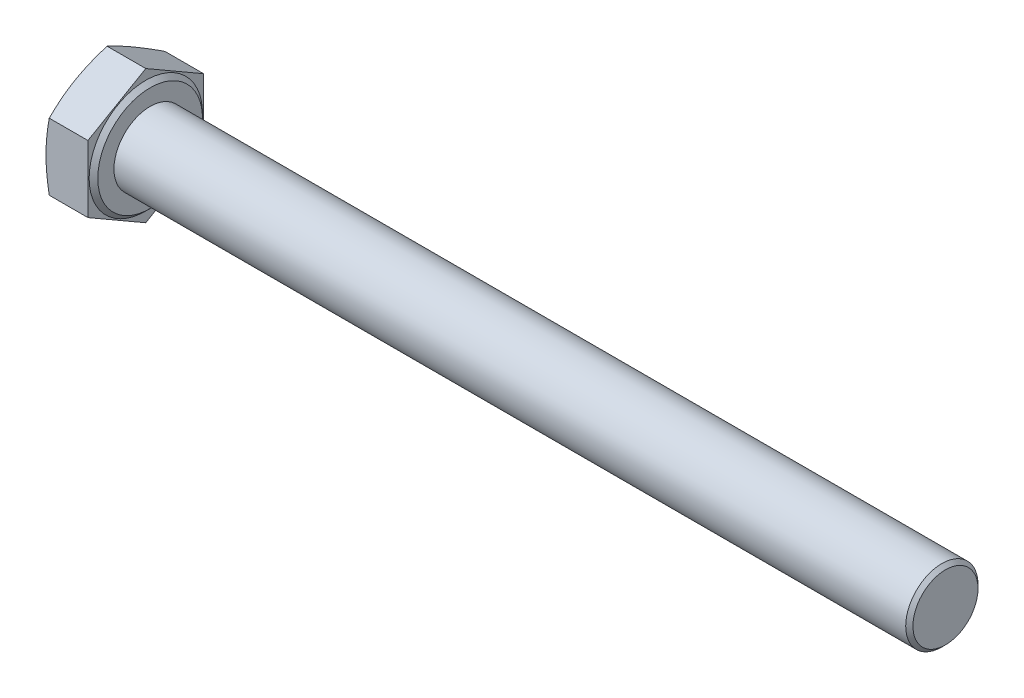
SolidWorks part; units mm, degrees
ref_plane "Front" through (0, 0, 0) normal (0, 0, 1) x (1, 0, 0)
ref_plane "Top" through (0, 0, 0) normal (0, 1, 0) x (1, 0, 0)
ref_plane "Right" through (0, 0, 0) normal (1, 0, 0) x (0, 0, -1)
other "Configuration Table"
sketch "Sketch2" plane through (0, 0, 0) normal (1, 0, 0) x (0, 0, -1)
  line L1 (0, -9.2376) -> (8, -4.6188)
  line L2 (8, -4.6188) -> (8, 4.6188)
  line L3 (8, 4.6188) -> (0, 9.2376)
  line L4 (0, 9.2376) -> (-8, 4.6188)
  line L5 (-8, 4.6188) -> (-8, -4.6188)
  line L6 (-8, -4.6188) -> (0, -9.2376)
  circle A0 centre (0, 0) radius 8 construction
  dimension "s" = 16
extrude "BaseHead" add sketch "Sketch2" along normal blind 6.4
sketch "Sketch3" plane through (0, 0, 0) normal (0, 0, 1) x (1, 0, 0)
  line L0 (6.4, 9.2376) -> (6.4, 7.235)
  line L2 (6.4, 7.235) -> (5.8, 7.835)
  line L3 (5.8, 7.835) -> (5.8, 9.2376)
  line L5 (5.8, 9.2376) -> (6.4, 9.2376)
  line L6 (-0.9571, 0) -> (7.6478, 0) construction
  line L7 (6.4, 9.2376) -> (0, 9.2376) construction
  dimension "D1" = 45
  dimension "c" = 0.6
  dimension "dw" = 14.47
revolve "BearingFace" cut sketch "Sketch3" angle 360 about L6
sketch "Sketch4" plane through (0, 0, 0) normal (0, 0, 1) x (1, 0, 0)
  line L0 (-0.4935, 0) -> (3.5626, 0) construction
  line L2 (0, 9.2376) -> (0.4505, 9.2376)
  line L4 (0.4505, 9.2376) -> (0, 8)
  line L6 (0, 8) -> (0, 9.2376)
  line L7 (5.8, 9.2376) -> (0, 9.2376) construction
  dimension "D1" = 20
  dimension "D2" = 16
revolve "HeadChamfer" cut sketch "Sketch4" angle 360 about L0
ref_plane "Plane1" through (30.4, 0, 0) normal (1, 0, 0) x (0, 0, -1)
sketch "Sketch5" plane through (6.4, 0, 0) normal (1, 0, 0) x (0, 0, -1)
  circle A0 centre (0, 0) radius 5
  dimension "d" = 10
extrude "BaseBody" add sketch "Sketch5" along normal blind 110
cosmetic thread "ThreadCosmetic1" [suppressed] parameters "D1"=86, "D2"=8.376
chamfer "Chamfer1" distance 0.5 angle 45 1 edges at (116.4, 0, -5)
fillet "HeadFillet" [suppressed] radius 0.4
sketch "Sketch6" plane through (0, 0, 0) normal (0, 0, 1) x (1, 0, 0)
  line L0 (115.088, 5.812) -> (115.9, 5.812)
  line L1 (115.9, 5.812) -> (115.9, 5)
  line L2 (115.9, 5) -> (115.494, 4.2968)
  line L3 (115.494, 4.2968) -> (115.088, 5)
  line L4 (115.088, 5) -> (115.088, 5.812)
  line L5 (115.9, -5) -> (115.9, 5) construction
  line L6 (115.9, 5) -> (6.4, 5) construction
  dimension "D1" = 0.812
revolve "Cut-Revolve10" [suppressed] cut sketch "Sketch6" angle 360
pattern_linear "LPattern10" [suppressed] count 88
equation "\"D2@Sketch4\" = \"s@Sketch2\""
equation "\"D1@Chamfer1\" = 0.05 * \"d@Sketch5\""
equation "\"D1@ThreadCosmetic1\" = \"l@BaseBody\" - \"lg@Plane1\""
equation "\"D1@Sketch6\" =  ( \"d@Sketch5\" - \"D2@ThreadCosmetic1\" )  / 2"
equation "\"pitch@LPattern10\" = 1.2 * \"D1@Sketch6\""
equation "\"D1@LPattern10\" = \"D1@ThreadCosmetic1\" / \"pitch@LPattern10\""
